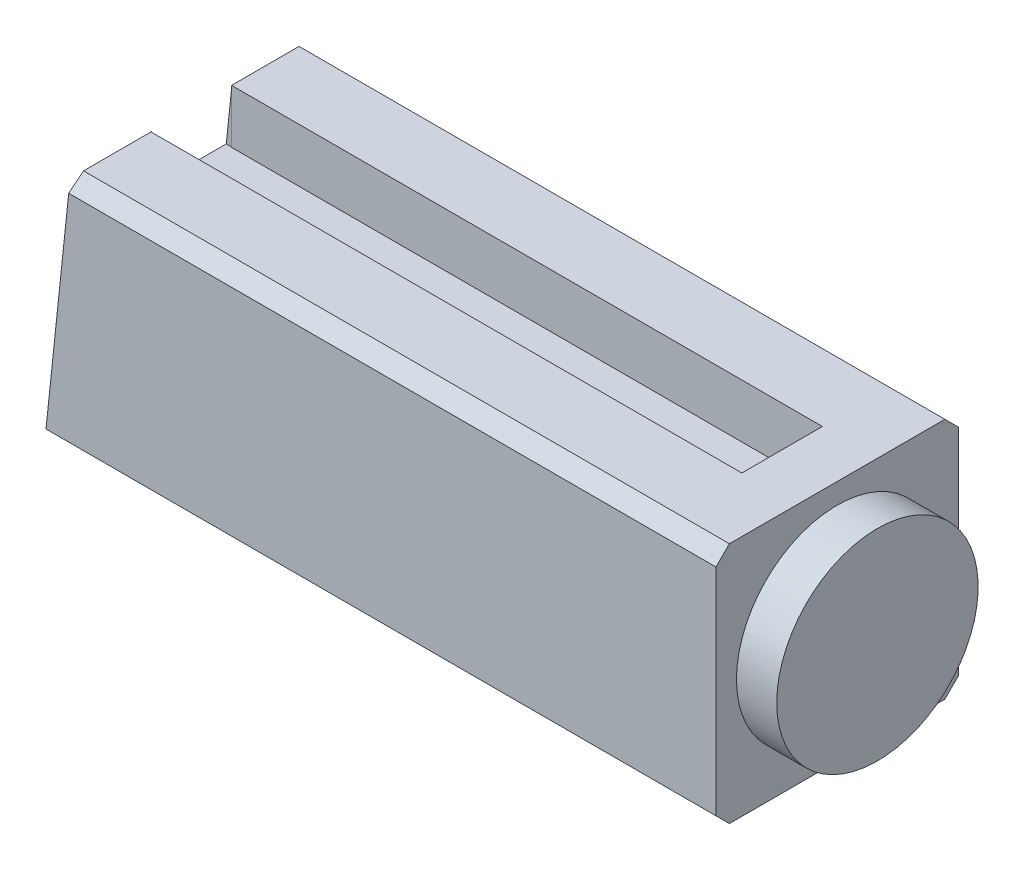
SolidWorks part; units mm, degrees
ref_plane "Front Plane" through (0, 0, 0) normal (0, 0, 1) x (1, 0, 0)
ref_plane "Top Plane" through (0, 0, 0) normal (0, 1, 0) x (1, 0, 0)
ref_plane "Right Plane" through (0, 0, 0) normal (1, 0, 0) x (0, 0, -1)
sketch "Sketch1" plane through (0, 0, 0) normal (0, 0, 1) x (1, 0, 0)
  line L0 (-6.1087, 2.2923) -> (-6.5913, -2.2923)
  line L1 (-6.1087, -2.2923) -> (6.1087, -2.2923)
  line L2 (-6.1087, -2.2923) -> (-6.1087, 2.2923)
  line L3 (-6.1087, 2.2923) -> (6.1087, 2.2923)
  line L4 (6.1087, -2.2923) -> (6.1087, 2.2923)
  line L5 (-6.1087, -2.2923) -> (6.1087, 2.2923) construction
  line L6 (-6.1087, 2.2923) -> (6.1087, -2.2923) construction
  line L7 (-6.5913, -2.2923) -> (-6.1087, -2.2923)
  line L8 (-6.1087, 2.2923) -> (-6.1087, -2.2923)
  point P0 (0, 0)
  dimension "D1" = 12.2174
  dimension "D2" = 4.5847
  dimension "D3" = 0.4826
extrude "Boss-Extrude1" add sketch "Sketch1" along normal blind 4.5847 contours L0 L7 L2 | L1 L4 L3 L2
sketch "Sketch2" plane through (0, 2.2923, 0) normal (0, 1, 0) x (1, 0, 0)
  line L0 (-6.1087, -4.5847) -> (-6.1087, 0) construction
  line L1 (-6.1087, -3.0543) -> (5.0673, -3.0543)
  line L2 (-6.1087, -3.0543) -> (-6.1087, -1.5303)
  line L3 (-6.1087, -1.5303) -> (5.0673, -1.5304)
  line L4 (5.0673, -3.0543) -> (5.0673, -1.5304)
  line L5 (-2.5216, 0) -> (2.5216, 0) construction
  dimension "D1" = 11.176
  dimension "D2" = 1.524
  dimension "D3" = 1.5303
extrude "Cut-Extrude1" cut sketch "Sketch2" against normal blind 1.016
sketch "Sketch4" plane through (-6.1087, 0, 0) normal (1, 0, 0) x (0, 0, -1)
  line L0 (-4.5847, 2.2923) -> (0, 2.2923) construction
  line L1 (-3.048, 2.2923) -> (-1.524, 2.2923)
  line L2 (-3.048, 2.2923) -> (-3.048, 1.2763)
  line L3 (-3.048, 1.2763) -> (-1.524, 1.2763)
  line L4 (-1.524, 2.2923) -> (-1.524, 1.2763)
  line L6 (0, 2.5216) -> (0, -2.5216) construction
  dimension "D1" = 1.016
  dimension "D2" = 1.524
  dimension "D3" = 1.524
extrude "Cut-Extrude3" cut sketch "Sketch4" against normal through all
sketch "Sketch5" plane through (6.1087, 0, 0) normal (1, 0, 0) x (0, 0, -1)
  line L0 (-2.2923, 2.2923) -> (-2.2923, -2.2923) construction
  line L1 (-4.5847, 2.2923) -> (0, 2.2923) construction
  line L2 (-4.5847, -2.2923) -> (0, -2.2923) construction
  circle A0 centre (-2.2923, 0) radius 1.905
  dimension "D1" = 3.81
extrude "Boss-Extrude3" add sketch "Sketch5" along normal blind 0.762
chamfer "Chamfer1" distance 0.254 angle 45 4 edges at (0, 2.2924, 0) (-0.2413, -2.2923, 4.5847) (-0.2413, -2.2923, 0) (0, 2.2924, 4.5847)
sketch "Sketch6" plane through (0, 0, 1.5303) normal (0, 0, 1) x (1, 0, 0)
  line L0 (5.0673, 2.2923) -> (5.0673, 1.2763)
  line L1 (5.0673, 1.2763) -> (4.0513, 1.2763)
  line L2 (4.0513, 1.2763) -> (5.0673, 2.2923)
  dimension "D1" = 1.016
  dimension "D2" = 1.016
extrude "Boss-Extrude4" add sketch "Sketch6" along normal up to next
